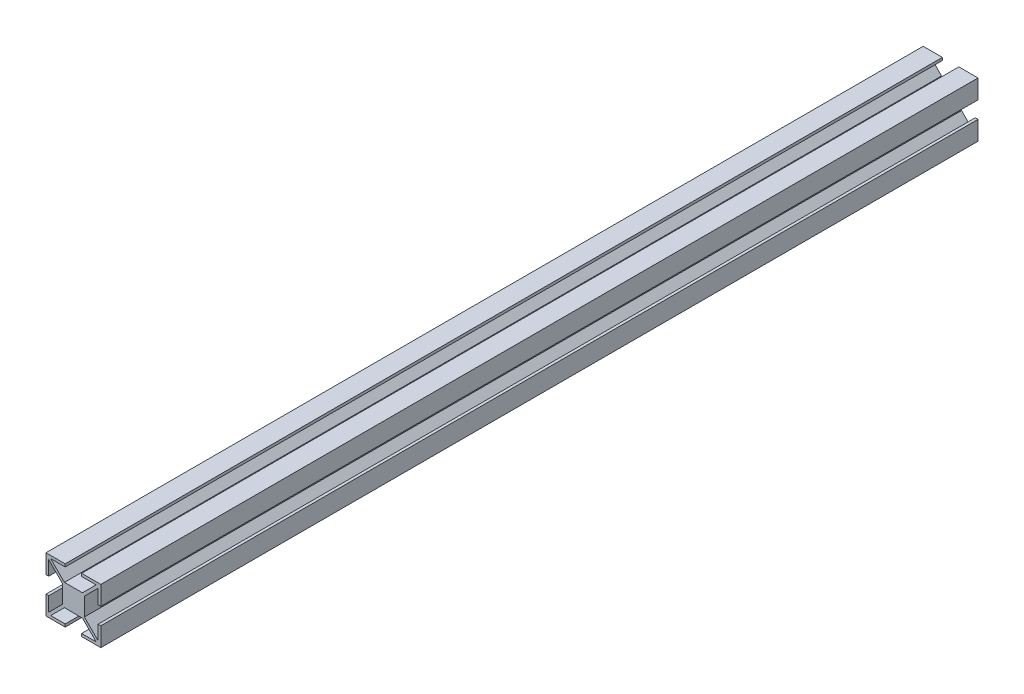
SolidWorks part; units mm, degrees
ref_plane "Front Plane" through (0, 0, 0) normal (0, 0, 1) x (1, 0, 0)
ref_plane "Top Plane" through (0, 0, 0) normal (0, 1, 0) x (1, 0, 0)
ref_plane "Right Plane" through (0, 0, 0) normal (1, 0, 0) x (0, 0, -1)
sketch "Sketch2" plane through (0, 0, 0) normal (0, 0, 1) x (1, 0, 0)
  line L0 (-10, 10) -> (-3, 10)
  line L1 (-3.2929, -4) -> (3.2929, -4)
  line L2 (-4, -3.2929) -> (-4, 3.2929)
  line L3 (-3.2929, 4) -> (3.2929, 4)
  line L4 (4, -3.2929) -> (4, 3.2929)
  line L5 (-4, -4) -> (4, 4) construction
  line L6 (-4, 4) -> (4, -4) construction
  line L7 (-10, -10) -> (10, -10) construction
  line L8 (-10, -10) -> (-10, 10) construction
  line L9 (-10, 10) -> (10, 10) construction
  line L10 (10, -10) -> (10, 10) construction
  line L11 (-10, -10) -> (10, 10) construction
  line L12 (-10, 10) -> (10, -10) construction
  line L13 (-10, 10) -> (-10, 3.074)
  line L14 (0, -11) -> (0, 11) construction
  line L15 (10, 10) -> (10, 3.074)
  line L16 (10, 10) -> (3, 10)
  line L17 (11, 0) -> (-11, 0) construction
  line L18 (10, -10) -> (10, -3.074)
  line L19 (10, -10) -> (3, -10)
  line L20 (-10, -10) -> (-3, -10)
  line L21 (-10, -10) -> (-10, -3.074)
  line L22 (-9, 8.2929) -> (-9, 3.074)
  line L23 (-8.2929, 9) -> (-3, 9)
  line L24 (-3, 10) -> (-3, 9)
  line L25 (-10, 3.074) -> (-9, 3.074)
  line L26 (-3, -10) -> (-3, -9)
  line L27 (-8.2929, -9) -> (-3, -9)
  line L28 (-9, -8.2929) -> (-9, -3.074)
  line L29 (-10, -3.074) -> (-9, -3.074)
  line L30 (10, 3.074) -> (9, 3.074)
  line L31 (9, 8.2929) -> (9, 3.074)
  line L32 (8.2929, 9) -> (3, 9)
  line L33 (3, 10) -> (3, 9)
  line L34 (3, -10) -> (3, -9)
  line L35 (8.2929, -9) -> (3, -9)
  line L36 (9, -8.2929) -> (9, -3.074)
  line L37 (10, -3.074) -> (9, -3.074)
  line L38 (-9, 9) -> (-3, 3) construction
  line L39 (-9, 8.2929) -> (-4, 3.2929)
  line L40 (-8.2929, 9) -> (-3.2929, 4)
  line L41 (-8.6464, 9.3536) -> (-2.6464, 3.3536) construction
  line L42 (-9.3536, 8.6464) -> (-3.3536, 2.6464) construction
  line L43 (-9, 9) -> (-3, 9) construction
  line L44 (-9, 9) -> (-9, 3.074) construction
  line L45 (9, 8.2929) -> (4, 3.2929)
  line L46 (8.2929, 9) -> (3.2929, 4)
  line L47 (9, -8.2929) -> (4, -3.2929)
  line L48 (8.2929, -9) -> (3.2929, -4)
  line L49 (-9, -8.2929) -> (-4, -3.2929)
  line L50 (-8.2929, -9) -> (-3.2929, -4)
  point P0 (0, 0)
  point P6 (0, 0)
  point P26 (-9, 5.6835)
  point P28 (-9, -5.6835)
  dimension "D1" = 8
  dimension "D2" = 8
  dimension "D3" = 20
  dimension "D4" = 20
  dimension "D5" = 1
  dimension "D8" = 45
  dimension "D9" = 6.5858
  dimension "D10" = 6.5858
  dimension "D11" = 1
  dimension "D6" = 0.5
  dimension "D7" = 0.5
extrude "Boss-Extrude1" add sketch "Sketch2" along normal blind 320.01
